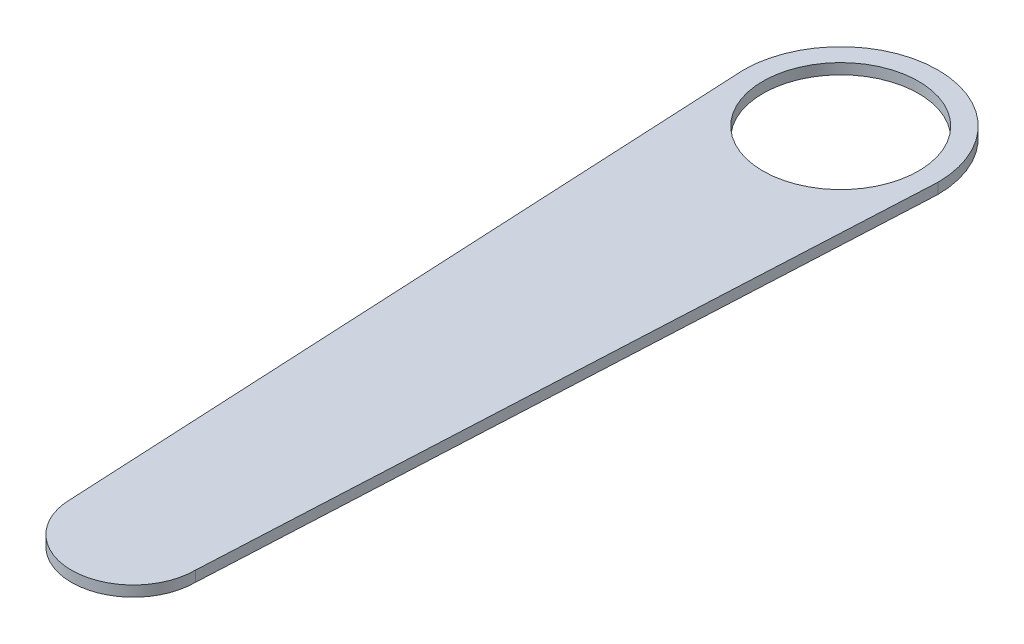
SolidWorks part; units mm, degrees
ref_plane "Front Plane" through (0, 0, 0) normal (0, 0, 1) x (1, 0, 0)
ref_plane "Top Plane" through (0, 0, 0) normal (0, 1, 0) x (1, 0, 0)
ref_plane "Right Plane" through (0, 0, 0) normal (1, 0, 0) x (0, 0, -1)
sketch "Sketch1" plane through (0, 0, 0) normal (0, 1, 0) x (1, 0, 0)
  line L0 (-27.5, 0) -> (-17.5, -200)
  line L2 (17.5, -200) -> (27.5, 0)
  circle A0 centre (0, 0) radius 27.5
  circle A1 centre (0, -200) radius 17.5
  dimension "D1" = 55
  dimension "D2" = 35
  dimension "D3" = 200
extrude "Boss-Extrude1" add sketch "Sketch1" along normal blind 3 contours L2 A0 L0 | A1 L2 A0 L0 | A1
sketch "Sketch2" plane through (0, 3, 0) normal (0, 1, 0) x (1, 0, 0)
  circle A0 centre (0, 0) radius 22
  dimension "D1" = 44
extrude "Cut-Extrude1" cut sketch "Sketch2" against normal through all
